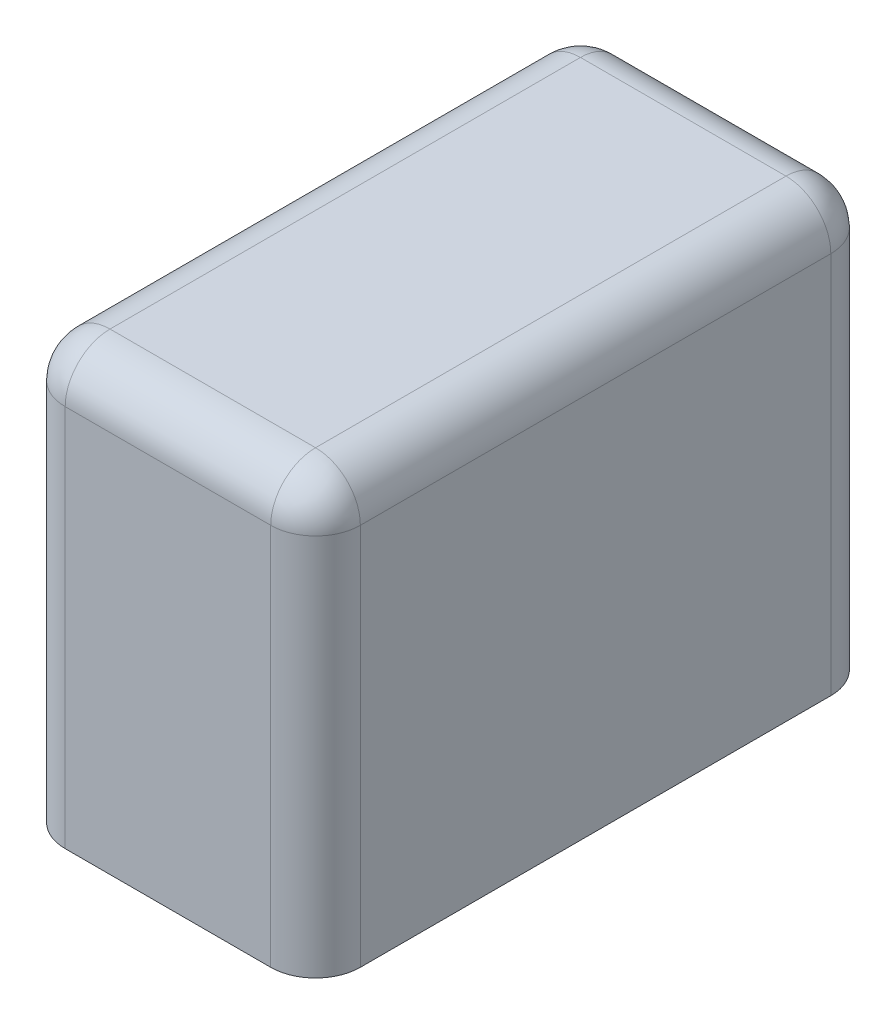
SolidWorks part; units mm, degrees
ref_plane "Front Plane" through (0, 0, 0) normal (0, 0, 1) x (1, 0, 0)
ref_plane "Top Plane" through (0, 0, 0) normal (0, 1, 0) x (1, 0, 0)
ref_plane "Right Plane" through (0, 0, 0) normal (1, 0, 0) x (0, 0, -1)
sketch "Sketch1" plane through (0, 0, 0) normal (0, 1, 0) x (1, 0, 0)
  line L1 (-13.175, 25) -> (13.175, 25)
  line L2 (-13.175, 25) -> (-13.175, -25)
  line L3 (-13.175, -25) -> (13.175, -25)
  line L4 (13.175, 25) -> (13.175, -25)
  line L5 (-13.175, 25) -> (13.175, -25) construction
  line L6 (-13.175, -25) -> (13.175, 25) construction
  line L7 (-10, 21.825) -> (10, 21.825)
  line L8 (-10, 21.825) -> (-10, -21.825)
  line L9 (-10, -21.825) -> (10, -21.825)
  line L10 (10, 21.825) -> (10, -21.825)
  line L11 (-10, 21.825) -> (10, -21.825) construction
  line L12 (-10, -21.825) -> (10, 21.825) construction
  point P0 (0, 0)
  point P6 (0, 0)
  dimension "D1" = 3.175
  dimension "D2" = 3.175
  dimension "D3" = 20
  dimension "D4" = 50
extrude "Boss-Extrude1" add sketch "Sketch1" along normal blind 35
sketch "Sketch2" plane through (0, 35, 0) normal (0, 1, 0) x (1, 0, 0)
  line L1 (-13.175, -25) -> (13.175, -25)
  line L2 (-13.175, -25) -> (-13.175, 25)
  line L3 (-13.175, 25) -> (13.175, 25)
  line L4 (13.175, -25) -> (13.175, 25)
extrude "Boss-Extrude2" add sketch "Sketch2" along normal blind 3.175
sketch "Sketch4" plane through (0, 0, 0) normal (0, -1, 0) x (1, 0, 0)
  line L0 (10, 21.825) -> (10, -21.825) construction
  line L2 (13.175, -25) -> (-13.175, -25) construction
  line L3 (-13.175, 0) -> (13.175, 0) construction
  line L4 (-13.175, -25) -> (-13.175, 25) construction
  line L5 (13.175, 25) -> (13.175, -25) construction
  line L17 (-8.6, -20) -> (-8.6, -21.825)
  line L18 (10, -21.825) -> (-10, -21.825) construction
  line L19 (-1.4, -20) -> (-1.4, -21.825)
  line L20 (-8.6, 21.825) -> (-1.4, 21.825)
  line L21 (-1.4, 20) -> (-1.4, 21.825)
  line L22 (-8.6, -21.825) -> (-1.4, -21.825)
  line L23 (-8.6, 20) -> (-8.6, 21.825)
  arc A4 (-1.4, -20) -> (-8.6, -20) centre (-5, -20) ccw
  arc A5 (-1.4, 20) -> (-8.6, 20) centre (-5, 20) cw
  dimension "D1" = 7.2
  dimension "D2" = 5
  dimension "D3" = 15
extrude "Boss-Extrude3" add sketch "Sketch4" against normal blind 5
fillet "Fillet1" radius 4 8 edges at (-13.175, 38.175, 0) (-13.175, 19.0875, -25) (0, 38.175, -25) (13.175, 19.0875, -25) (13.175, 38.175, 0) (0, 38.175, 25) (13.175, 19.0875, 25) (-13.175, 19.0875, 25)
sketch "Sketch6" plane through (-13.175, 0, 0) normal (-1, 0, 0) x (0, 0, 1)
  line L0 (0, 34.175) -> (0, 0) construction
  line L5 (21, 34.175) -> (-21, 34.175) construction
  line L8 (-21, 0) -> (21, 0) construction
  line L9 (-10, 18.175) -> (0, 18.175) construction
  line L10 (-5, 23.175) -> (5, 23.175)
  line L11 (-5, 23.175) -> (-5, 18.175)
  line L12 (-5, 18.175) -> (5, 18.175)
  line L13 (5, 23.175) -> (5, 18.175)
  line L14 (-5, 23.175) -> (5, 18.175) construction
  line L15 (-5, 18.175) -> (5, 23.175) construction
  point P6 (0, 20.675)
  dimension "D1" = 10
  dimension "D2" = 5
  dimension "D3" = 0
extrude "Cut-Extrude3" cut sketch "Sketch6" against normal blind 3.175
sketch "Sketch8" plane through (0, 0, 0) normal (0, -1, 0) x (1, 0, 0)
  line L0 (-13.175, 0) -> (13.175, 0) construction
  line L1 (-13.175, -21) -> (-13.175, 21) construction
  line L2 (13.175, 21) -> (13.175, -21) construction
  circle A0 centre (-5, -20) radius 3.05
  circle A1 centre (-5, 20) radius 3.05
  dimension "D1" = 6.1
extrude "Cut-Extrude5" cut sketch "Sketch8" against normal blind 2.7
sketch "Sketch9" plane through (13.175, 0, 0) normal (1, 0, 0) x (0, 0, -1)
  line L0 (0, 34.175) -> (0, 0) construction
  line L2 (-21, 0) -> (21, 0) construction
  line L3 (16.5, 11.6) -> (16.5, 7.6)
  line L4 (-12.25, 11.6) -> (-6.25, 11.6)
  line L5 (-12.25, 11.6) -> (-12.25, 7.6)
  line L6 (-12.25, 7.6) -> (-6.25, 7.6)
  line L7 (-6.25, 11.6) -> (-6.25, 7.6)
  line L8 (22.5, 7.6) -> (16.5, 7.6)
  line L9 (22.5, 11.6) -> (22.5, 7.6)
  line L10 (22.5, 11.6) -> (16.5, 11.6)
  line L11 (21, 34.175) -> (-21, 34.175) construction
  dimension "D1" = 6
  dimension "D2" = 4
  dimension "D4" = 7.6
  dimension "D3" = 22.75
  dimension "D5" = 6.25
  dimension "D7" = 0
  dimension "D8" = 4
  dimension "D6" = 6
extrude "Boss-Extrude4" add sketch "Sketch9" against normal blind 12.5 from surface at -3.175 starting at face at (10, 17.5, 0)
sketch "Sketch10" plane through (0, 7.6, 0) normal (0, -1, 0) x (1, 0, 0)
  line L0 (-16.5229, 0) -> (15.3543, 0) construction
  line L1 (10, 21.825) -> (10, -21.825) construction
  circle A0 centre (3.75, 8.575) radius 1
  circle A1 centre (3.75, -18.825) radius 1
  dimension "D3" = 2
  dimension "D1" = 27.4
  dimension "D2" = 6.25
  dimension "D4" = 8.575
extrude "Cut-Extrude6" cut sketch "Sketch10" against normal blind 15.675
equation "\"D8@Sketch9\"=\"D2@Sketch9\""
equation "\"D6@Sketch9\"=\"D1@Sketch9\""
